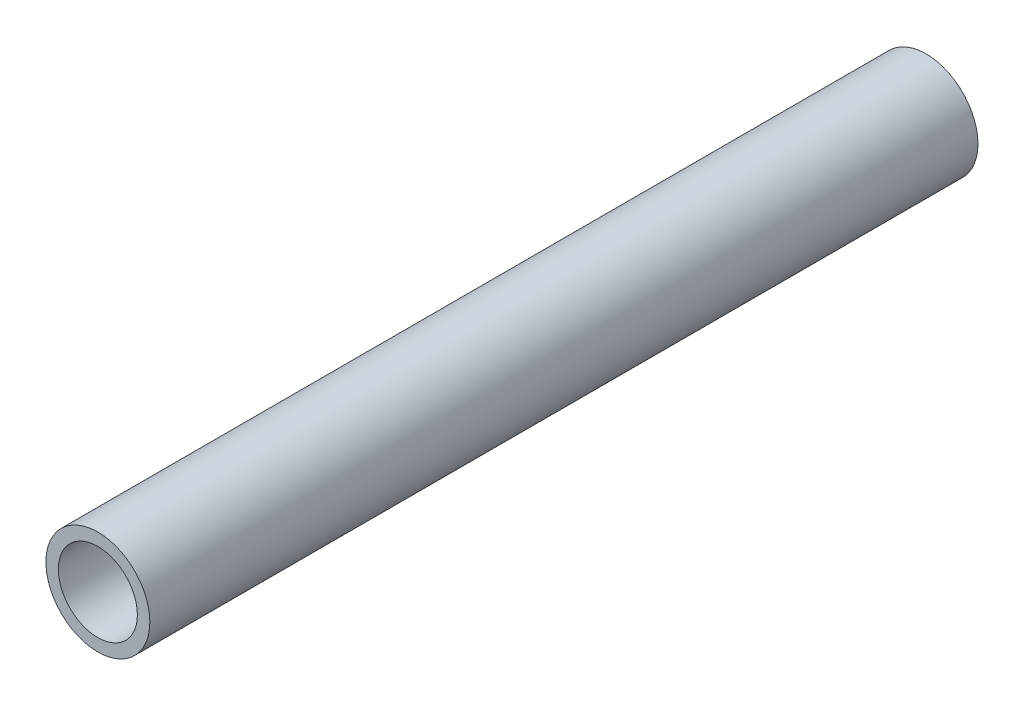
SolidWorks part; units mm, degrees
material "Plain Carbon Steel"
ref_plane "Front Plane" through (0, 0, 0) normal (0, 0, 1) x (1, 0, 0)
ref_plane "Top Plane" through (0, 0, 0) normal (0, 1, 0) x (1, 0, 0)
ref_plane "Right Plane" through (0, 0, 0) normal (1, 0, 0) x (0, 0, -1)
sketch "Sketch1" plane through (0, 0, 0) normal (0, 0, 1) x (1, 0, 0)
  circle A0 centre (0, 0) radius 16.7005
extrude "Extrude-Thin1" add sketch "Sketch1" along normal blind 266.192 thin thin type one direction reverse wall 4.0005
